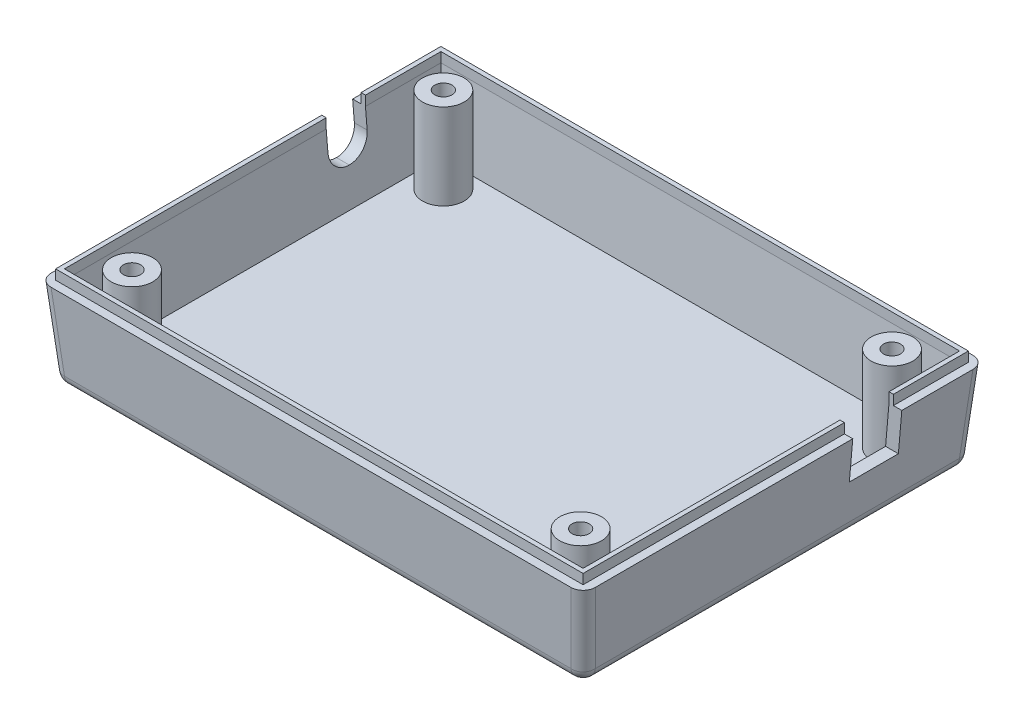
SolidWorks part; units mm, degrees
ref_plane "Спереди" through (0, 0, 0) normal (0, 0, 1) x (1, 0, 0)
ref_plane "Сверху" through (0, 0, 0) normal (0, 1, 0) x (1, 0, 0)
ref_plane "Справа" through (0, 0, 0) normal (1, 0, 0) x (0, 0, -1)
ref_plane "Плоскость наушники" through (-55.5, 0, 0) normal (1, 0, 0) x (0, 0, -1)
ref_plane "Плоскость2" through (55.5, 0, 0) normal (1, 0, 0) x (0, 0, -1)
sketch "Эскиз1" plane through (0, 0, 0) normal (0, 1, 0) x (1, 0, 0)
  line L1 (-55.5, 41) -> (55.5, 41)
  line L2 (-55.5, 41) -> (-55.5, -41)
  line L3 (-55.5, -41) -> (55.5, -41)
  line L4 (55.5, 41) -> (55.5, -41)
  point P4 (-55.5, 0)
  point P5 (0, 41)
  dimension "D1" = 111
  dimension "D2" = 82
extrude "Бобышка-Вытянуть1" add sketch "Эскиз1" against normal blind 18 draft 5
shell "Оболочка1" thickness 2.6
fillet "Скругление1" radius 2.5 8 edges at (0, -18, -39.4252) (53.9252, -18, 0) (0, -18, 39.4252) (-53.9252, -18, 0) (-54.7126, -9, 40.2126) (-54.7126, -9, -40.2126) (54.7126, -9, -40.2126) (54.7126, -9, 40.2126)
sketch "Эскиз2" plane through (0, 0, 0) normal (0, 1, 0) x (1, 0, 0)
  line L0 (-53.7901, 39.2901) -> (-53.7901, -39.2901)
  line L1 (-52.8901, 38.3901) -> (52.8901, 38.3901)
  line L2 (-52.8901, 38.3901) -> (-52.8901, -38.3901)
  line L3 (-52.8901, -38.3901) -> (52.8901, -38.3901)
  line L4 (52.8901, 38.3901) -> (52.8901, -38.3901)
  line L5 (-53.7901, -39.2901) -> (53.7901, -39.2901)
  line L6 (53.7901, 39.2901) -> (53.7901, -39.2901)
  line L7 (-53.7901, 39.2901) -> (53.7901, 39.2901)
  dimension "D1" = 0.9
extrude "Бобышка-Вытянуть2" add sketch "Эскиз2" along normal blind 2
sketch "Эскиз4" plane through (0, -15.4, 0) normal (0, 1, 0) x (1, 0, 0)
  circle A0 centre (-45.75, 31.75) radius 4.25
  dimension "D1" = 8.5
  dimension "D2" = 45.75
  dimension "D3" = 31.75
extrude "Бобышка-Вытянуть3" add sketch "Эскиз4" along normal blind 17.5
mirror "Зеркальное отражение1" about plane through (0, 0, 0) normal (1, 0, 0) of "Бобышка-Вытянуть3"
mirror "Зеркальное отражение2" about plane through (0, 0, 0) normal (0, 0, 1) of "Зеркальное отражение1", "Бобышка-Вытянуть3"
sketch "Эскиз5" plane through (0, -18, 0) normal (0, 1, 0) x (1, 0, 0)
  circle A0 centre (-45.75, 31.75) radius 3.25
  dimension "D1" = 6.5
  dimension "D2" = 45.75
  dimension "D3" = 31.75
extrude "Вырез-Вытянуть2" cut sketch "Эскиз5" along normal blind 17.5
mirror "Зеркальное отражение3" about plane through (0, 0, 0) normal (1, 0, 0) of "Вырез-Вытянуть2"
mirror "Зеркальное отражение4" about plane through (0, 0, 0) normal (0, 0, 1) of "Зеркальное отражение3", "Вырез-Вытянуть2"
sketch "Эскиз6" plane through (0, 2.1, 0) normal (0, 1, 0) x (-1, 0, 0)
  circle A0 centre (45.75, -31.75) radius 1.75
  dimension "D1" = 3.5
  dimension "D2" = 45.75
  dimension "D3" = 31.75
extrude "Вырез-Вытянуть3" cut sketch "Эскиз6" against normal blind 3
mirror "Зеркальное отражение5" about plane through (0, 0, 0) normal (1, 0, 0) of "Вырез-Вытянуть3"
mirror "Зеркальное отражение6" about plane through (0, 0, 0) normal (0, 0, 1) of "Зеркальное отражение5", "Вырез-Вытянуть3"
sketch "Эскиз7" plane through (-55.5, 0, 0) normal (1, 0, 0) x (0, 0, -1)
  line L0 (19, -8) -> (19, 2) construction
  line L1 (19.001, -8) -> (18.999, -8)
  line L2 (23, -4.001) -> (23, 2)
  line L3 (23, 2) -> (15, 2)
  line L4 (15, -4.001) -> (15, 2)
  line L7 (39.2901, 2) -> (-39.2901, 2) construction
  arc A0 (15, -4.001) -> (18.999, -8) centre (18.999, -4.001) ccw
  arc A1 (19.001, -8) -> (23, -4.001) centre (19.001, -4.001) ccw
  point P11 (23, -8)
  dimension "D4" = 3.999
  dimension "D1" = 10
  dimension "D2" = 8
  dimension "D3" = 60
extrude "Вырез-Вытянуть4" cut sketch "Эскиз7" along normal blind 5
sketch "Эскиз8" plane through (55.5, 0, 0) normal (1, 0, 0) x (0, 0, -1)
  line L0 (19, -8) -> (19, 2) construction
  line L1 (14, 2) -> (24, 2)
  line L2 (14, 2) -> (14, -8)
  line L3 (14, -8) -> (24, -8)
  line L4 (24, 2) -> (24, -8)
  line L5 (-39.2901, 2) -> (39.2901, 2) construction
  dimension "D1" = 10
  dimension "D2" = 10
  dimension "D3" = 60
extrude "Вырез-Вытянуть5" cut sketch "Эскиз8" against normal blind 5
